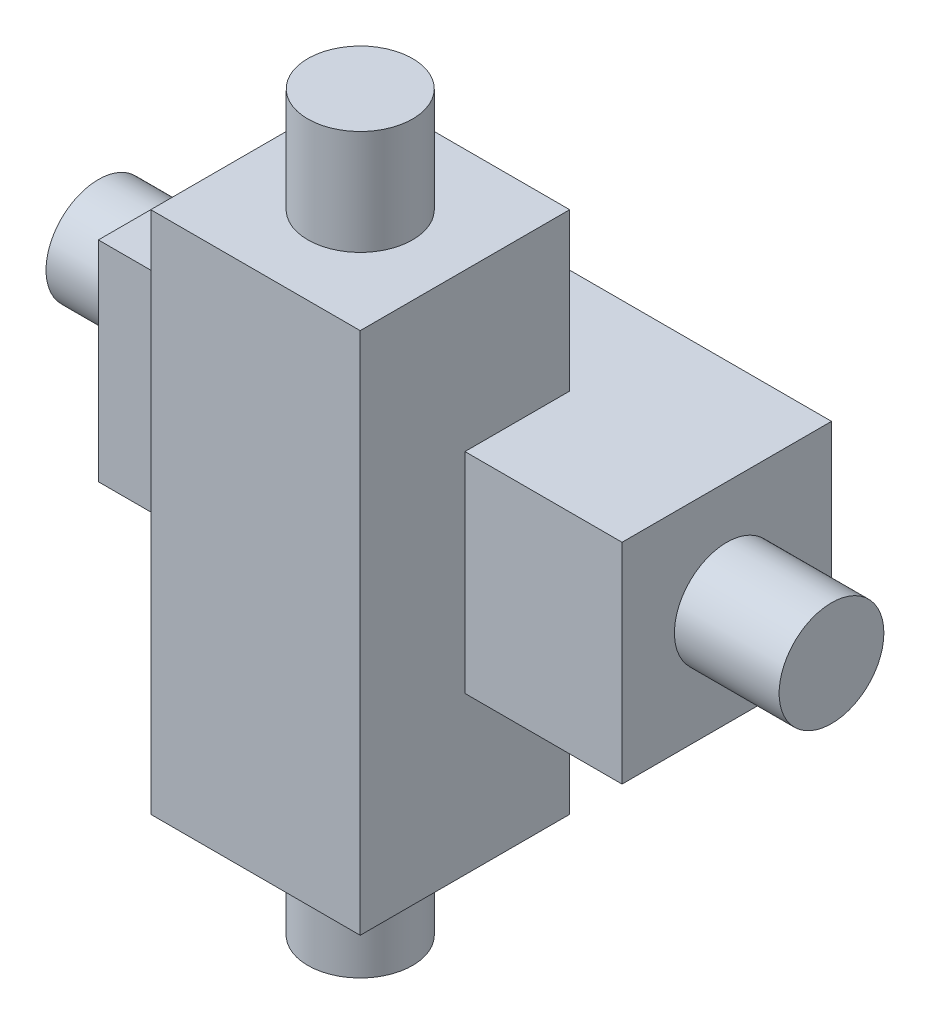
SolidWorks part; units mm, degrees
ref_plane "Front Plane" through (0, 0, 0) normal (0, 0, 1) x (1, 0, 0)
ref_plane "Top Plane" through (0, 0, 0) normal (0, 1, 0) x (1, 0, 0)
ref_plane "Right Plane" through (0, 0, 0) normal (1, 0, 0) x (0, 0, -1)
sketch "Sketch1" plane through (0, 0, 0) normal (0, 1, 0) x (1, 0, 0)
  line L1 (-1, 1) -> (1, 1)
  line L2 (-1, 1) -> (-1, -1)
  line L3 (-1, -1) -> (1, -1)
  line L4 (1, 1) -> (1, -1)
  line L5 (-1, 1) -> (1, -1) construction
  line L6 (-1, -1) -> (1, 1) construction
  point P0 (0, 0)
  dimension "D1" = 2
  dimension "D2" = 2
extrude "Boss-Extrude1" add sketch "Sketch1" along normal mid plane 5
sketch "Sketch2" plane through (0, 0, 0) normal (1, 0, 0) x (0, 0, -1)
  line L5 (1, 2.5) -> (1, -2.5) construction
  line L6 (0, 1) -> (2, 1)
  line L7 (0, 1) -> (0, -1)
  line L8 (0, -1) -> (2, -1)
  line L9 (2, 1) -> (2, -1)
  line L10 (0, 1) -> (2, -1) construction
  line L11 (0, -1) -> (2, 1) construction
  point P0 (1, 0)
  dimension "D1" = 2
  dimension "D2" = 2
extrude "Boss-Extrude2" add sketch "Sketch2" along normal mid plane 5
sketch "Sketch3" plane through (0, 0, 0) normal (0, 1, 0) x (1, 0, 0)
  circle A0 centre (0, 0) radius 0.5
  dimension "D1" = 1
extrude "Boss-Extrude3" add sketch "Sketch3" along normal mid plane 7
sketch "Sketch5" plane through (0, 0, 0) normal (1, 0, 0) x (0, 0, -1)
  line L0 (0, -1) -> (2, 1) construction
  circle A0 centre (1, 0) radius 0.5
  dimension "D1" = 1
extrude "Boss-Extrude4" add sketch "Sketch5" along normal mid plane 7
